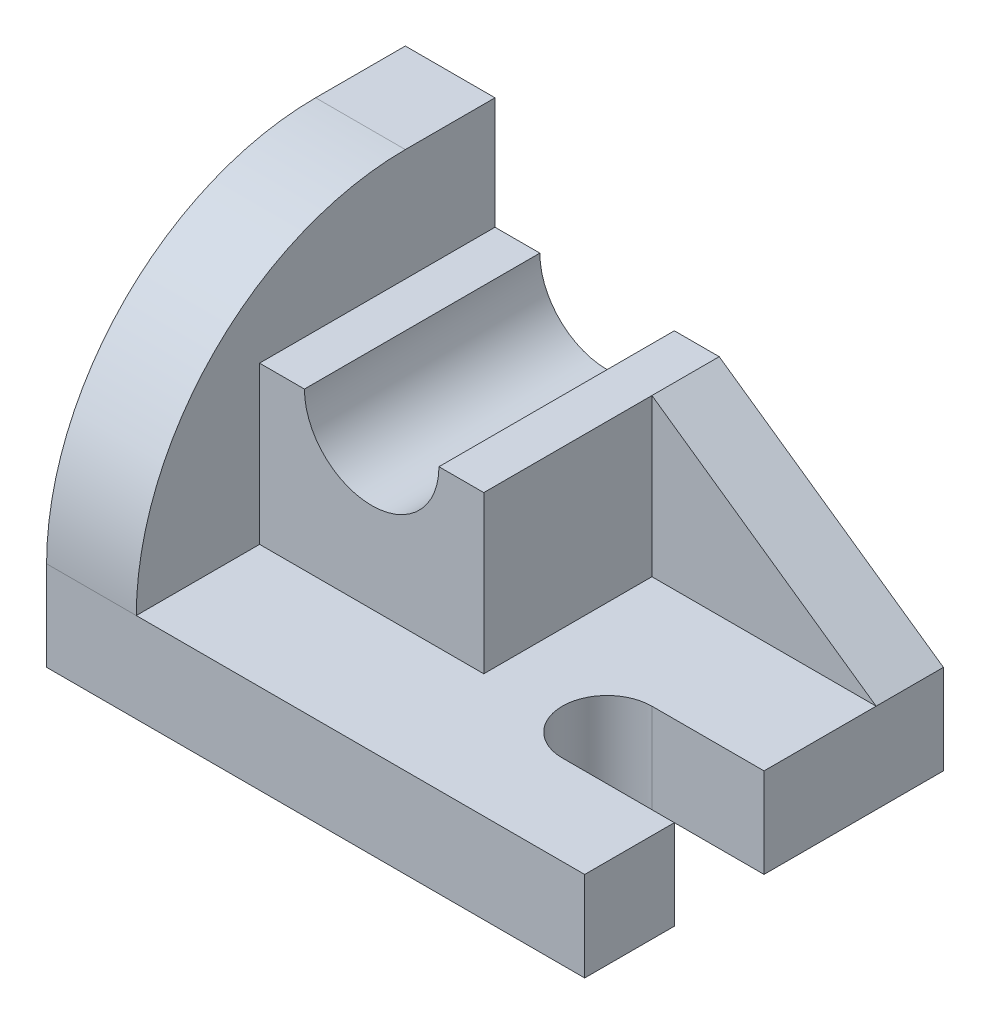
SolidWorks part; units mm, degrees
ref_plane "Front Plane" through (0, 0, 0) normal (0, 0, 1) x (1, 0, 0)
ref_plane "Top Plane" through (0, 0, 0) normal (0, 1, 0) x (1, 0, 0)
ref_plane "Right Plane" through (0, 0, 0) normal (1, 0, 0) x (0, 0, -1)
sketch "Sketch3" plane through (0, 0, 0) normal (0, 1, 0) x (1, 0, 0)
  line L1 (0, 0) -> (96, 0)
  line L2 (0, 0) -> (0, 64)
  line L3 (0, 64) -> (96, 64)
  line L4 (96, 0) -> (96, 64)
  dimension "D1" = 96
  dimension "D2" = 64
extrude "Boss-Extrude1" add sketch "Sketch3" along normal blind 16
sketch "Sketch4" plane through (0, 16, 0) normal (0, 1, 0) x (1, 0, 0)
  line L0 (96, 24) -> (76, 24) construction
  line L1 (96, 0) -> (96, 64) construction
  line L2 (96, 16) -> (76, 16)
  line L3 (96, 32) -> (76, 32)
  line L4 (0, 0) -> (96, 0) construction
  arc A0 (96, 16) -> (96, 32) centre (96, 24) ccw
  arc A1 (76, 32) -> (76, 16) centre (76, 24) ccw
  point P4 (86, 24)
  point P9 (86, 16)
  dimension "D1" = 20
  dimension "D2" = 16
  dimension "D3" = 16
extrude "Cut-Extrude1" cut sketch "Sketch4" against normal blind 16
sketch "Sketch5" plane through (0, 0, 0) normal (-1, 0, 0) x (0, 0, 1)
  line L1 (-64, 0) -> (0, 0)
  line L2 (-64, 0) -> (-64, 64)
  line L3 (-64, 64) -> (-48, 64)
  line L4 (0, 0) -> (0, 16)
  arc A0 (-48, 64) -> (0, 16) centre (-48, 16) cw
  point P7 (0, 64)
  dimension "D3" = 48
  dimension "D1" = 64
  dimension "D2" = 64
extrude "Boss-Extrude2" add sketch "Sketch5" against normal blind 16
sketch "Sketch6" plane through (0, 16, 0) normal (0, 1, 0) x (1, 0, 0)
  line L0 (16, 0) -> (96, 0) construction
  line L1 (16, 64) -> (56, 64)
  line L2 (16, 64) -> (16, 22)
  line L3 (16, 22) -> (56, 22)
  line L4 (56, 64) -> (56, 22)
  dimension "D1" = 40
  dimension "D2" = 22
extrude "Boss-Extrude3" add sketch "Sketch6" along normal blind 28
sketch "Sketch7" plane through (0, 0, -22) normal (0, 0, 1) x (1, 0, 0)
  line L0 (16, 44) -> (56, 44) construction
  circle A0 centre (36, 44) radius 12
  dimension "D1" = 24
extrude "Cut-Extrude2" cut sketch "Sketch7" against normal blind 46
sketch "Sketch11" plane through (0, 0, -64) normal (0, 0, -1) x (-1, 0, 0)
  line L0 (-56, 44) -> (-96, 16)
  line L10 (-16, 44) -> (-24, 44)
  line L11 (-48, 44) -> (-56, 44)
  line L12 (-56, 44) -> (-56, 16)
  line L13 (-56, 16) -> (-96, 16)
  line L14 (-96, 16) -> (-96, 0)
  line L15 (-96, 0) -> (0, 0)
  line L16 (0, 0) -> (0, 64)
  line L17 (0, 64) -> (-16, 64)
  line L18 (-16, 64) -> (-16, 44)
  line L21 (-56, 44) -> (-56, 16)
  line L22 (-56, 16) -> (-96, 16)
  arc A1 (-48, 44) -> (-24, 44) centre (-36, 44) ccw
  dimension "D1" = 0
extrude "Boss-Extrude4" add sketch "Sketch11" against normal blind 12
